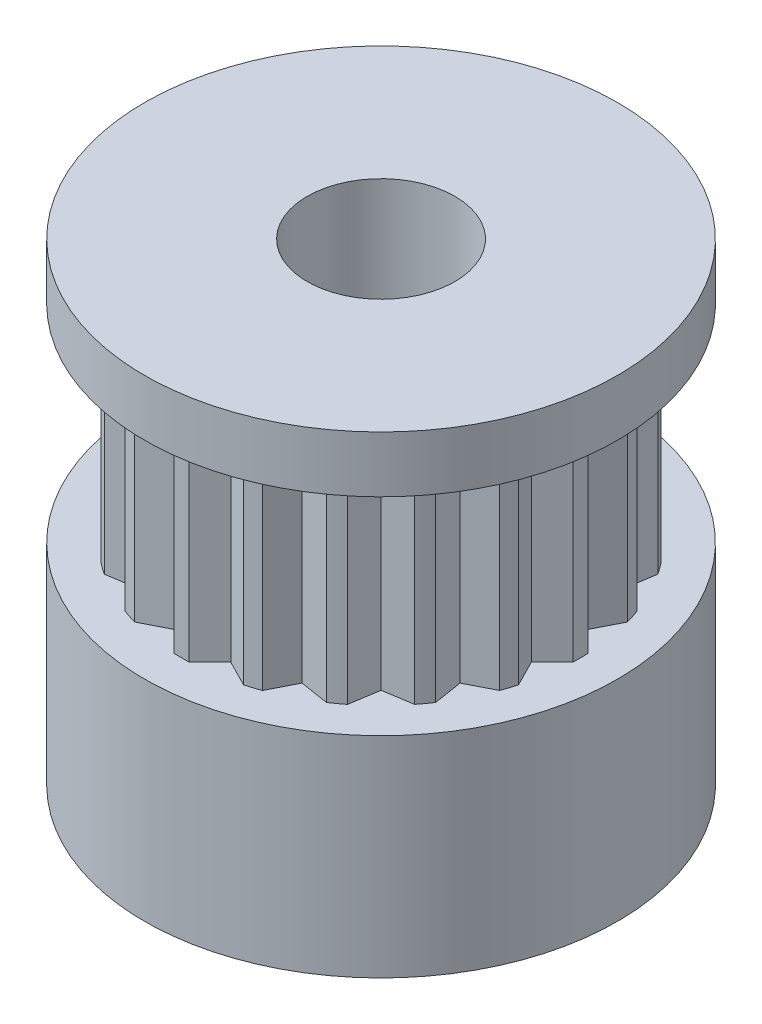
SolidWorks part; units mm, degrees
material "Chrome Stainless Steel"
ref_plane "Front Plane" through (0, 0, 0) normal (0, 0, 1) x (1, 0, 0)
ref_plane "Top Plane" through (0, 0, 0) normal (0, 1, 0) x (1, 0, 0)
ref_plane "Right Plane" through (0, 0, 0) normal (1, 0, 0) x (0, 0, -1)
sketch "Sketch2" plane through (0, 0, 0) normal (0, 0, 1) x (1, 0, 0)
  line L0 (0, 0) -> (0, 16) construction
  line L1 (-2.5, 0) -> (-8, 0)
  line L2 (-8, 0) -> (-8, 7.1)
  line L3 (-8, 7.1) -> (-6.11, 7.1)
  line L4 (-6.11, 7.1) -> (-6.11, 14.1)
  line L5 (-6.11, 14.1) -> (-8, 14.1)
  line L6 (-8, 14.1) -> (-8, 16)
  line L7 (-8, 16) -> (-2.5, 16)
  line L8 (-2.5, 16) -> (-2.5, 0)
  dimension "D1" = 8
  dimension "D2" = 16
  dimension "D3" = 6.11
  dimension "D4" = 2.5
  dimension "D5" = 7.1
  dimension "D6" = 7
revolve "Revolve1" add sketch "Sketch2" angle 360 about L0
sketch "Sketch3" plane through (0, 7.1, 0) normal (0, 1, 0) x (1, 0, 0)
  line L0 (-6, 1) -> (-6, -1)
  line L1 (-6, -1) -> (-7, 0)
  line L2 (-7, 0) -> (-6, 1)
  line L3 (-6, 0) -> (0, 0) construction
  dimension "D1" = 2
  dimension "D2" = 1
  dimension "D3" = 6
extrude "Boss-Extrude1" add sketch "Sketch3" along normal up to surface (7 mm away) up to face at (0, 14.1, -6.11)
pattern_circular "CirPattern1" count 20 over 360 about axis through (0, 0, 0) along (0, 1, 0) of "Boss-Extrude1"
sketch "Sketch4" plane through (0, 7.1, 0) normal (0, 1, 0) x (1, 0, 0)
  circle A0 centre (0, 0) radius 7.5
  circle A1 centre (0, 0) radius 6.75
  dimension "D1" = 15
  dimension "D2" = 13.5
extrude "Cut-Extrude1" cut sketch "Sketch4" along normal up to surface (7 mm away) up to face at (0, 14.1, -8)
